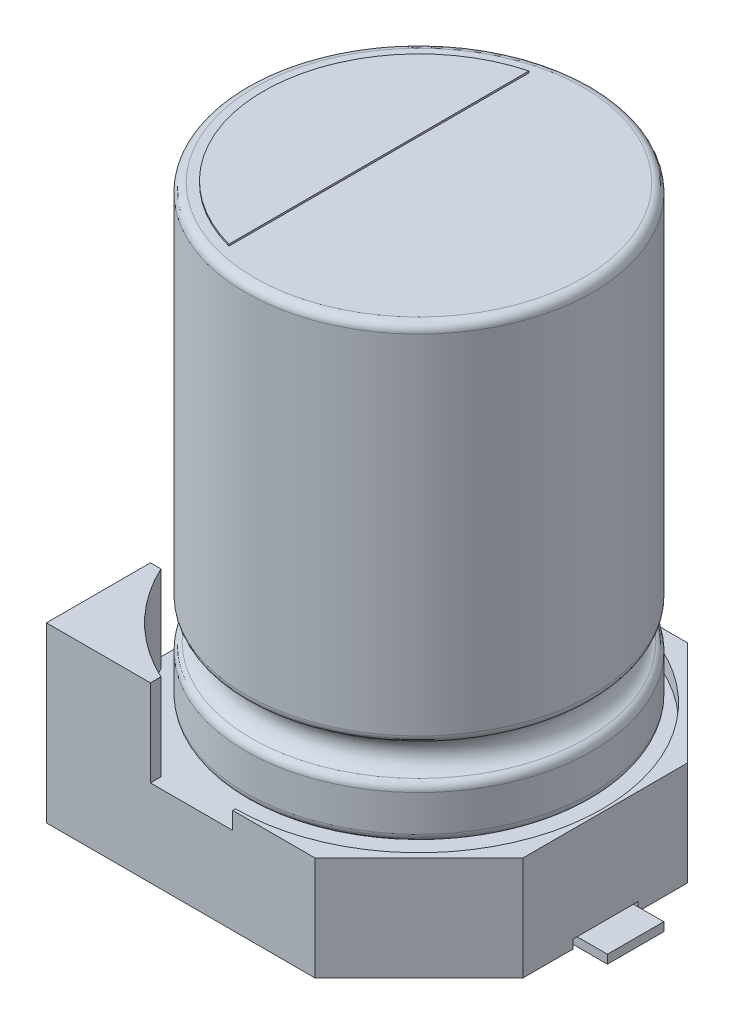
SolidWorks part; units mm, degrees
ref_plane "Спереди" through (0, 0, 0) normal (0, 0, 1) x (1, 0, 0)
ref_plane "Сверху" through (0, 0, 0) normal (0, 1, 0) x (1, 0, 0)
ref_plane "Справа" through (0, 0, 0) normal (1, 0, 0) x (0, 0, -1)
sketch "Эскиз1" plane through (0, 0, 0) normal (0, 1, 0) x (1, 0, 0)
  line L0 (0, -4.1246) -> (0, 3.4908) construction
  line L2 (2.15, -2.15) -> (-2.15, -2.15)
  line L3 (2.15, -2.15) -> (2.15, 2.15)
  line L4 (2.15, 2.15) -> (-2.15, 2.15)
  line L5 (-2.15, -2.15) -> (-2.15, 2.15)
  line L6 (2.15, -2.15) -> (-2.15, 2.15) construction
  line L7 (2.15, 2.15) -> (-2.15, -2.15) construction
  point P3 (0, 0)
  dimension "D1" = 4.3
  dimension "D2" = 4.3
extrude "Бобышка-Вытянуть1" add sketch "Эскиз1" along normal blind 1
sketch "Эскиз2a" plane through (0, 1, 0) normal (0, 1, 0) x (1, 0, 0)
  line L0 (-0.4339, 0) -> (2.682, 0) construction
  line L1 (2.15, 2.15) -> (0.95, 2.15) construction
  line L2 (2.15, 2.15) -> (2.15, 0.95) construction
  line L3 (2.15, 0.95) -> (0.95, 0.95) construction
  line L4 (0.95, 2.15) -> (0.95, 0.95) construction
  line L5 (0.95, -2.15) -> (0.95, -0.95) construction
  line L6 (2.15, -0.95) -> (0.95, -0.95) construction
  line L7 (2.15, -2.15) -> (2.15, -0.95) construction
  line L8 (2.15, -2.15) -> (0.95, -2.15) construction
  line L9 (2.15, 0.95) -> (2.15, 2.15)
  line L10 (2.15, 2.15) -> (0.95, 2.15)
  line L11 (0.95, 2.15) -> (2.15, 0.95)
  line L12 (2.15, -0.95) -> (2.15, -2.15)
  line L13 (2.15, -2.15) -> (0.95, -2.15)
  line L14 (0.95, -2.15) -> (2.15, -0.95)
  dimension "D1" = 1.2
  dimension "D2" = 1.2
extrude "Вырез-Вытянуть3" cut sketch "Эскиз2a" against normal through all
sketch "Эскиз4" plane through (0, 1, 0) normal (0, 1, 0) x (1, 0, 0)
  line L0 (-2.15, 0.95) -> (-2.0286, 0.95)
  line L1 (-2.15, 2.15) -> (-0.95, 2.15)
  line L2 (-2.15, 2.15) -> (-2.15, 0.95)
  line L3 (-0.95, 2.0286) -> (-0.95, 2.15)
  line L4 (0.3435, 0) -> (-2.6459, 0) construction
  line L5 (-0.95, -2.0286) -> (-0.95, -2.15)
  line L6 (-2.15, -2.15) -> (-2.15, -0.95)
  line L7 (-2.15, -2.15) -> (-0.95, -2.15)
  line L8 (-2.15, -0.95) -> (-2.0286, -0.95)
  arc A0 (-0.95, 2.0286) -> (-2.0286, 0.95) centre (0, 0) ccw
  arc A1 (-0.95, -2.0286) -> (-2.0286, -0.95) centre (0, 0) cw
  dimension "D1" = 1.2
  dimension "D2" = 1.2
extrude "Бобышка-Вытянуть2" add sketch "Эскиз4" along normal blind 1
sketch "Эскиз5" plane through (0, 1, 0) normal (0, 1, 0) x (1, 0, 0)
  line L0 (0, 2.1185) -> (0, 2.15)
  line L1 (0.95, 2.15) -> (-0.95, 2.15) construction
  line L2 (0, 2.15) -> (0.95, 2.15)
  line L3 (0.95, 2.15) -> (2.15, 0.95)
  line L4 (2.15, 0.95) -> (2.15, -0.95)
  line L5 (2.15, -0.95) -> (0.95, -2.15)
  line L6 (0.95, -2.15) -> (0, -2.15)
  line L7 (-0.95, -2.15) -> (0.95, -2.15) construction
  line L8 (0, -2.15) -> (0, -2.1185)
  arc A0 (0, 2.1185) -> (0, -2.1185) centre (0, 0) cw
extrude "Бобышка-Вытянуть3" add sketch "Эскиз5" along normal blind 0.2
ref_plane "Плоскость1" through (0, 0, 0) normal (1, 0, 0) x (0, 0, -1)
sketch "Эскиз9" plane through (0, 0, 0) normal (1, 0, 0) x (0, 0, -1)
  line L0 (0, -0.3167) -> (0, 6.4) construction
  line L1 (-0.95, 1.2) -> (0.95, 1.2) construction
  line L2 (0, 1.2) -> (2, 1.2) construction
  line L3 (0, 1.2) -> (0, 6.4) construction
  line L4 (0, 6.4) -> (2, 6.4) construction
  line L5 (2, 1.2) -> (2, 6.4) construction
  line L6 (2.0286, 2) -> (0.95, 2) construction
  line L7 (0, 1.2) -> (2, 1.2) construction
  line L8 (0, 1.2) -> (0, 2) construction
  line L9 (0, 2) -> (2, 2) construction
  line L10 (2, 1.2) -> (2, 2) construction
  line L11 (2, 1.8) -> (2, 1.2)
  line L12 (2, 1.2) -> (0, 1.2)
  line L13 (0, 1.2) -> (0, 6.4)
  line L14 (0, 6.4) -> (2, 6.4)
  line L15 (2, 6.4) -> (2, 2.2)
  arc A0 (2, 2.2) -> (2, 1.8) centre (2, 2) ccw
  dimension "D3" = 0.2
  dimension "D1" = 2
  dimension "D2" = 5.2
revolve "Повернуть1" add sketch "Эскиз9" angle 360 about L0
fillet "Скругление1" radius 0.1 4 edges at (0, 6.4, -2) (0, 1.2, -2) (0, 1.8, -2) (0, 2.2, -2)
sketch "Эскиз10" plane through (0, 0, 0) normal (0, -1, 0) x (1, 0, 0)
  line L0 (-2.15, 0) -> (2.15, 0) construction
  line L1 (2.15, 0.325) -> (-2.15, 0.325) construction
  line L2 (0.5, -0.325) -> (-0.5, -0.325) construction
  line L3 (0.5, -0.325) -> (0.5, 0.325) construction
  line L4 (0.5, 0.325) -> (-0.5, 0.325) construction
  line L5 (-0.5, -0.325) -> (-0.5, 0.325) construction
  line L6 (0.5, -0.325) -> (-0.5, 0.325) construction
  line L7 (0.5, 0.325) -> (-0.5, -0.325) construction
  line L8 (-2.15, -0.325) -> (2.15, -0.325) construction
  line L9 (2.15, 0.95) -> (2.15, -0.95) construction
  line L10 (-2.15, -2.15) -> (-2.15, 2.15) construction
  line L11 (-2.15, 0.375) -> (2.15, 0.375) construction
  line L12 (0.45, -0.375) -> (-0.45, -0.375) construction
  line L13 (0.45, -0.375) -> (0.45, 0.375) construction
  line L14 (0.45, 0.375) -> (-0.45, 0.375) construction
  line L15 (-0.45, -0.375) -> (-0.45, 0.375) construction
  line L16 (0.45, -0.375) -> (-0.45, 0.375) construction
  line L17 (0.45, 0.375) -> (-0.45, -0.375) construction
  line L18 (-2.15, -0.375) -> (2.15, -0.375) construction
  line L19 (-2.15, 0.325) -> (-2.15, 0.375)
  line L20 (-2.15, 0.375) -> (-0.45, 0.375)
  line L21 (-0.45, 0.375) -> (-0.45, -0.375)
  line L22 (-0.45, -0.375) -> (-2.15, -0.375)
  line L23 (-2.15, -0.375) -> (-2.15, -0.325)
  line L24 (-2.15, -0.325) -> (-0.5, -0.325)
  line L25 (-0.5, -0.325) -> (-0.5, 0.325)
  line L26 (-0.5, 0.325) -> (-2.15, 0.325)
  line L27 (2.15, 0.375) -> (0.45, 0.375)
  line L28 (0.45, 0.375) -> (0.45, -0.375)
  line L29 (0.45, -0.375) -> (2.15, -0.375)
  line L30 (2.15, -0.375) -> (2.15, -0.325)
  line L31 (2.15, -0.325) -> (0.5, -0.325)
  line L32 (0.5, -0.325) -> (0.5, 0.325)
  line L33 (0.5, 0.325) -> (2.15, 0.325)
  line L34 (2.15, 0.325) -> (2.15, 0.375)
  point P3 (0, 0)
  point P14 (0, 0)
  dimension "D1" = 1
  dimension "D2" = 0.65
  dimension "D3" = 0.75
  dimension "D4" = 0.9
extrude "Вырез-Вытянуть4" cut sketch "Эскиз10" against normal blind 0.1
sketch "Эскиз11" plane through (2.15, 0, 0) normal (1, 0, 0) x (0, 0, -1)
  line L1 (-0.325, 0) -> (0.325, 0)
  line L2 (-0.325, 0) -> (-0.325, 0.1)
  line L3 (-0.325, 0.1) -> (0.325, 0.1)
  line L4 (0.325, 0) -> (0.325, 0.1)
extrude "Бобышка-Вытянуть6" add sketch "Эскиз11" along normal blind 0.35
sketch "Эскиз12" plane through (-2.15, 0, 0) normal (-1, 0, 0) x (0, 0, 1)
  line L1 (-0.325, 0) -> (0.325, 0)
  line L2 (-0.325, 0) -> (-0.325, 0.1)
  line L3 (-0.325, 0.1) -> (0.325, 0.1)
  line L4 (0.325, 0) -> (0.325, 0.1)
extrude "Бобышка-Вытянуть7" add sketch "Эскиз12" along normal blind 0.35
sketch "Эскиз13" plane through (0, 6.4, 0) normal (0, 1, 0) x (1, 0, 0)
  line L0 (-0.4622, 1.7312) -> (-0.4622, -1.7312)
  arc A0 (-0.4622, 1.7312) -> (-0.4622, -1.7312) centre (0, 0) ccw
extrude "Бобышка-Вытянуть8" add sketch "Эскиз13" along normal blind 0.02
